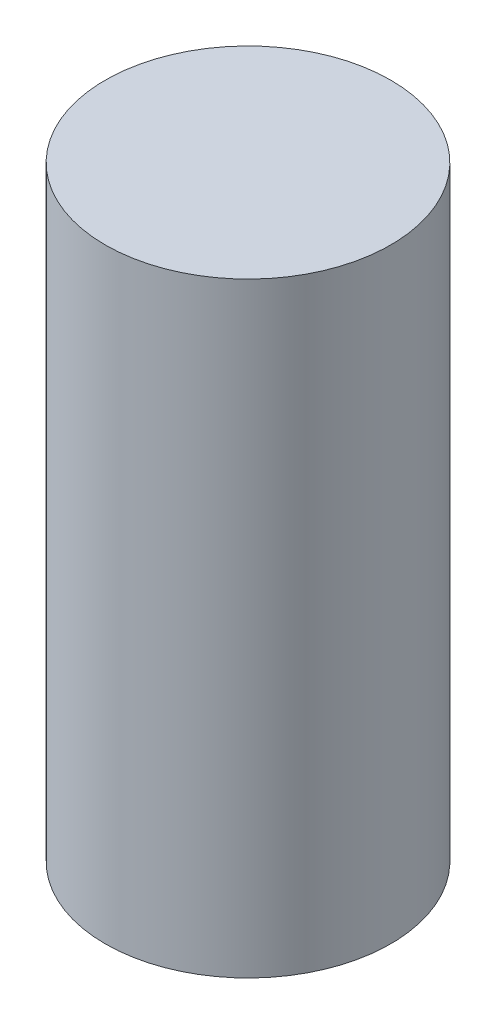
SolidWorks part; units mm, degrees
ref_plane "Front Plane" through (0, 0, 0) normal (0, 0, 1) x (1, 0, 0)
ref_plane "Top Plane" through (0, 0, 0) normal (0, 1, 0) x (1, 0, 0)
ref_plane "Right Plane" through (0, 0, 0) normal (1, 0, 0) x (0, 0, -1)
sketch "Profile Sketch" plane through (0, 0, 0) normal (0, 1, 0) x (1, 0, 0)
  circle A0 centre (0, 0) radius 50
  dimension "D1" = 100
extrude "Profile Extrude" add sketch "Profile Sketch" against normal blind 212
